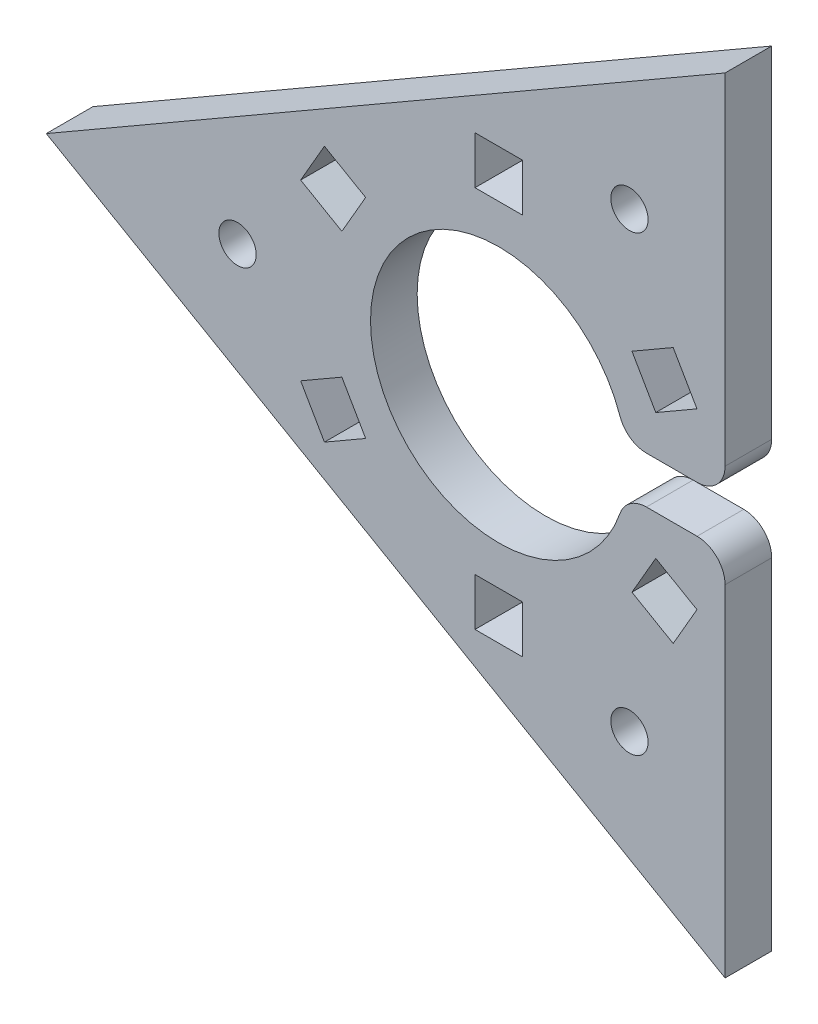
SolidWorks part; units mm, degrees
ref_plane "Front Plane" through (0, 0, 0) normal (0, 0, 1) x (1, 0, 0)
ref_plane "Top Plane" through (0, 0, 0) normal (0, 1, 0) x (1, 0, 0)
ref_plane "Right Plane" through (0, 0, 0) normal (1, 0, 0) x (0, 0, -1)
sketch "Sketch1" plane through (0, 0, 0) normal (0, 0, 1) x (1, 0, 0)
  line L0 (-26, 0) -> (26, 0) construction
  line L7 (-2.55, 23.05) -> (2.55, 23.05)
  line L8 (-2.55, 23.05) -> (-2.55, 17.95)
  line L9 (-2.55, 17.95) -> (2.55, 17.95)
  line L10 (2.55, 23.05) -> (2.55, 17.95)
  line L23 (0, 26) -> (0, -26) construction
  line L24 (21.2369, 9.3166) -> (16.8202, 6.7666)
  line L25 (14.2702, 11.1834) -> (16.8202, 6.7666)
  line L26 (18.6869, 13.7334) -> (14.2702, 11.1834)
  line L27 (18.6869, 13.7334) -> (21.2369, 9.3166)
  line L28 (18.6869, -13.7334) -> (14.2702, -11.1834)
  line L29 (16.8202, -6.7666) -> (14.2702, -11.1834)
  line L30 (21.2369, -9.3166) -> (16.8202, -6.7666)
  line L31 (21.2369, -9.3166) -> (18.6869, -13.7334)
  line L32 (-2.55, -23.05) -> (-2.55, -17.95)
  line L33 (2.55, -17.95) -> (-2.55, -17.95)
  line L34 (2.55, -23.05) -> (2.55, -17.95)
  line L35 (2.55, -23.05) -> (-2.55, -23.05)
  line L36 (-21.2369, -9.3166) -> (-16.8202, -6.7666)
  line L37 (-14.2702, -11.1834) -> (-16.8202, -6.7666)
  line L38 (-18.6869, -13.7334) -> (-14.2702, -11.1834)
  line L39 (-18.6869, -13.7334) -> (-21.2369, -9.3166)
  line L40 (-18.6869, 13.7334) -> (-14.2702, 11.1834)
  line L41 (-16.8202, 6.7666) -> (-14.2702, 11.1834)
  line L42 (-21.2369, 9.3166) -> (-16.8202, 6.7666)
  line L43 (-21.2369, 9.3166) -> (-18.6869, 13.7334)
  line L44 (24.2487, 2.5) -> (13.5208, 2.5)
  line L45 (24.2487, -2.5) -> (13.5208, -2.5)
  line L46 (24.2487, 42) -> (24.2487, -42) construction
  line L47 (24.2487, -42) -> (-48.4974, 0) construction
  line L48 (-48.4974, 0) -> (24.2487, 42) construction
  line L49 (24.2487, 2.5) -> (24.2487, 42)
  line L50 (24.2487, 42) -> (-48.4974, 0)
  line L51 (-48.4974, 0) -> (24.2487, -42)
  line L52 (24.2487, -42) -> (24.2487, -2.5)
  line L53 (0, 0) -> (24.2487, 42) construction
  line L54 (-2.55, 20.5) -> (2.55, 20.5) construction
  circle A0 centre (0, 0) radius 13.75 construction
  arc A2 (13.5208, 2.5) -> (13.5208, -2.5) centre (0, 0) ccw
  circle A4 centre (14, 24.2487) radius 2
  circle A5 centre (14, -24.2487) radius 2
  circle A6 centre (-28, 0) radius 2
  point P40 (0, 0)
  point P48 (0, 0)
  point P50 (0, 0)
  dimension "D2" = 84
  dimension "D1" = 27.5
  dimension "D10" = 4
  dimension "D3" = 5.1
  dimension "D4" = 5.1
  dimension "D5" = 20.5
  dimension "D6" = 6
  dimension "D7" = 5
  dimension "D9" = 28
  dimension "D11" = 3
  dimension "D8" = 3
extrude "Boss-Extrude1" add sketch "Sketch1" along normal blind 5
fillet "Congé2" radius 3 4 edges at (13.5208, 2.5, 2.5) (13.5208, -2.5, 2.5) (24.2487, -2.5, 2.5) (24.2487, 2.5, 2.5)
